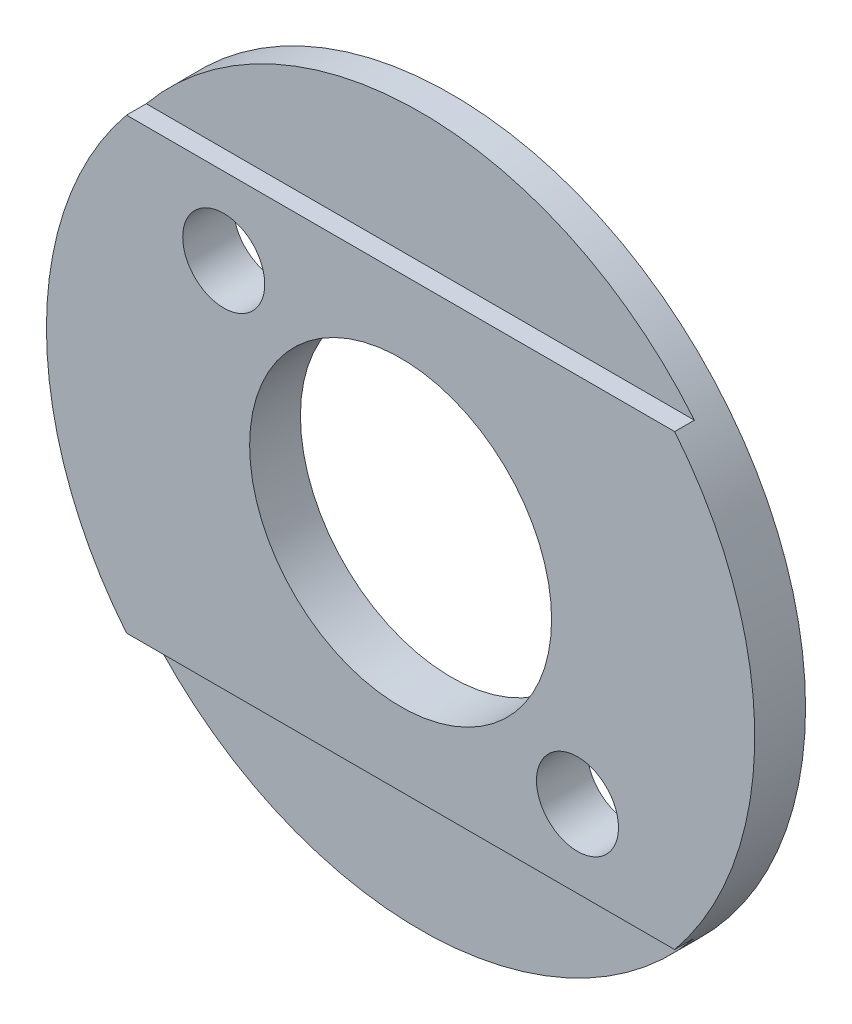
SolidWorks part; units mm, degrees
material "Custom Plastic"
ref_plane "X-Y Datum" through (0, 0, 0) normal (0, 0, 1) x (1, 0, 0)
ref_plane "X-Z Datum" through (0, 0, 0) normal (0, 1, 0) x (1, 0, 0)
ref_plane "Y-Z Datum" through (0, 0, 0) normal (1, 0, 0) x (0, 0, -1)
sketch "Sketch1" plane through (0, 0, 0) normal (0, 0, 1) x (1, 0, 0)
  line L1 (-54.8454, -59.0836) -> (1.429, -59.0836)
  line L3 (-54.8454, -97.1836) -> (1.429, -97.1836)
  line L4 (-54.8454, -60.0836) -> (1.429, -60.0836)
  line L5 (-54.8454, -96.1836) -> (1.429, -96.1836)
  circle A1 centre (-26.7082, -78.1336) radius 28.5
  circle A5 centre (-12.4743, -89.9508) radius 3.3
  circle A6 centre (-40.9421, -66.3164) radius 3.3
  circle A10 centre (-26.7082, -78.1336) radius 12.15
  dimension "D1" = 1
  dimension "D3" = 6.6
  dimension "D4" = 24.3
  dimension "D2" = 1
extrude "Boss-Extrude1" add sketch "Sketch1" along normal blind 1.5875 contours L4 A1 L5 A6 A5
sketch "Sketch2" plane through (0, 0, 0) normal (0, 0, -1) x (-1, 0, 0)
  line L0 (54.8454, -96.1836) -> (-1.429, -96.1836) construction
  line L1 (54.8454, -60.0836) -> (-1.429, -60.0836) construction
  line L2 (54.8454, -97.1836) -> (-1.429, -97.1836) construction
  line L3 (54.8454, -59.0836) -> (-1.429, -59.0836) construction
  line L4 (54.8454, -96.1836) -> (-1.429, -96.1836)
  line L5 (54.8454, -60.0836) -> (-1.429, -60.0836)
  line L6 (54.8454, -97.1836) -> (-1.429, -97.1836)
  line L7 (54.8454, -59.0836) -> (-1.429, -59.0836)
  circle A1 centre (40.9421, -66.3164) radius 3.3
  circle A2 centre (40.9421, -66.3164) radius 3.3
  circle A3 centre (12.4743, -89.9508) radius 3.3
  circle A4 centre (12.4743, -89.9508) radius 3.3
  circle A5 centre (26.7082, -78.1336) radius 28.5
  circle A6 centre (26.7082, -78.1336) radius 28.5
  circle M4 centre (40.9421, -66.3164) radius 3.3
  circle M5 centre (12.4743, -89.9508) radius 3.3
  line M6 (48.7638, -60.0836) -> (4.6527, -60.0836)
  arc M7 (4.6527, -60.0836) -> (4.6527, -96.1836) centre (26.7082, -78.1336) ccw
  line M8 (4.6527, -96.1836) -> (48.7638, -96.1836)
  arc M9 (48.7638, -96.1836) -> (48.7638, -60.0836) centre (26.7082, -78.1336) ccw
  dimension "D1" = 0
  dimension "D2" = 0
  dimension "D3" = 0
extrude "Boss-Extrude2" add sketch "Sketch2" along normal blind 2.5 contours M9 M6 M7 M8 M5 M4 | A6 L7 M6 | L7 A6 | A6 L6 M8 | L6 A6
